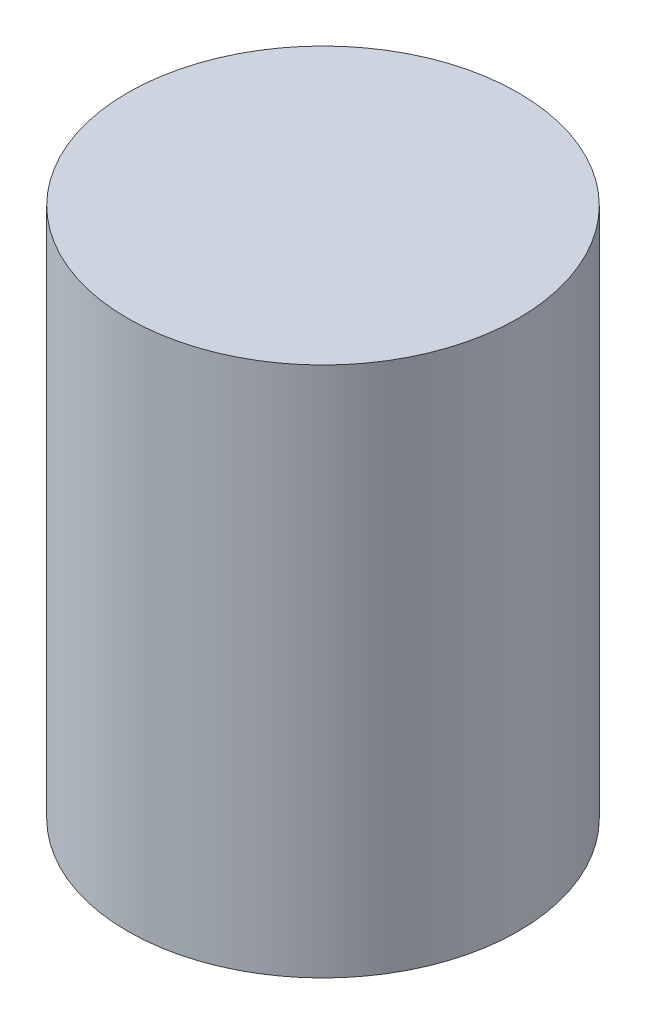
SolidWorks part; units mm, degrees
ref_plane "Plan de face" through (0, 0, 0) normal (0, 0, 1) x (1, 0, 0)
ref_plane "Plan de dessus" through (0, 0, 0) normal (0, 1, 0) x (1, 0, 0)
ref_plane "Plan de droite" through (0, 0, 0) normal (1, 0, 0) x (0, 0, -1)
sketch "Esquisse1" plane through (0, 0, 0) normal (0, 1, 0) x (1, 0, 0)
  circle A0 centre (0, 0) radius 73.61
  dimension "D1" = 147.22
extrude "Boss.-Extru.1" add sketch "Esquisse1" along normal blind 200
